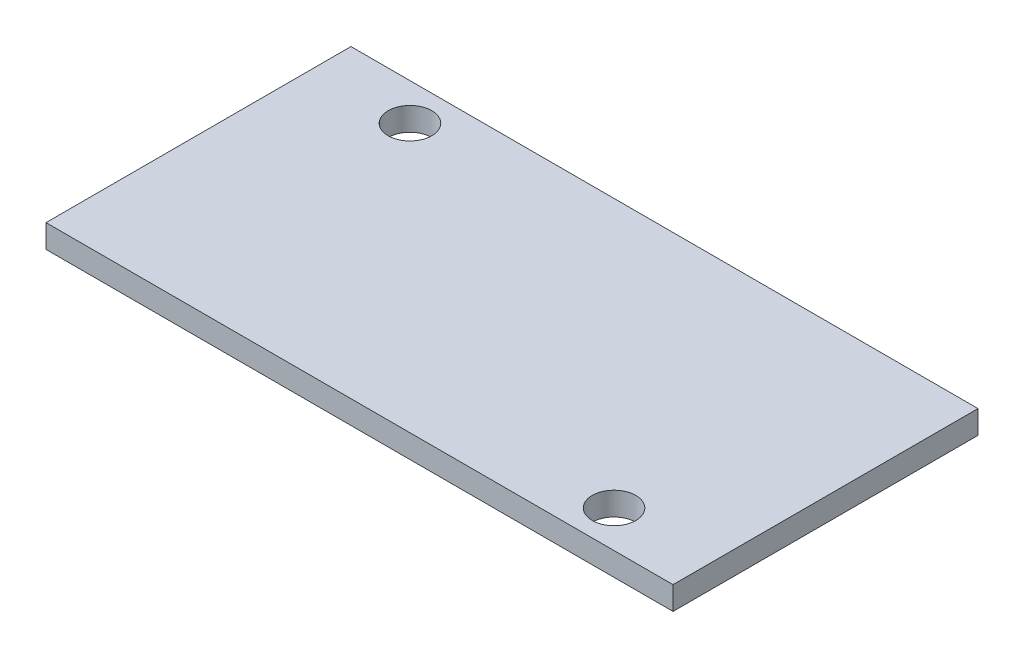
SolidWorks part; units mm, degrees
ref_plane "前视基准面" through (0, 0, 0) normal (0, 0, 1) x (1, 0, 0)
ref_plane "上视基准面" through (0, 0, 0) normal (0, 1, 0) x (1, 0, 0)
ref_plane "右视基准面" through (0, 0, 0) normal (1, 0, 0) x (0, 0, -1)
sketch "草图1" plane through (0, 0, 0) normal (0, 1, 0) x (1, 0, 0)
  line L0 (0, -18.7925) -> (0, 34.5365) construction
  line L1 (-21.59, 10.5) -> (21.59, 10.5)
  line L2 (-21.59, 10.5) -> (-21.59, -10.5)
  line L3 (-21.59, -10.5) -> (21.59, -10.5)
  line L4 (21.59, 10.5) -> (21.59, -10.5)
  line L5 (-48.0579, 0) -> (50.1007, 0) construction
  dimension "D1" = 43.18
  dimension "D2" = 21
extrude "凸台-拉伸1" add sketch "草图1" along normal blind 1.6
sketch "草图2" plane through (0, 1.6, 0) normal (0, 1, 0) x (1, 0, 0)
  line L0 (-21.59, 10.5) -> (-21.59, -10.5) construction
  line L1 (21.59, 10.5) -> (-21.59, 10.5) construction
  line L2 (21.59, -10.5) -> (21.59, 10.5) construction
  line L4 (-21.59, -10.5) -> (21.59, -10.5) construction
  circle A0 centre (-14.986, 7.96) radius 1.5
  circle A1 centre (14.986, -7.96) radius 1.5
  dimension "D1" = 3
  dimension "D4" = 3
  dimension "D2" = 6.604
  dimension "D3" = 2.54
  dimension "D5" = 6.604
  dimension "D6" = 2.54
extrude "切除-拉伸1" cut sketch "草图2" against normal blind 10
